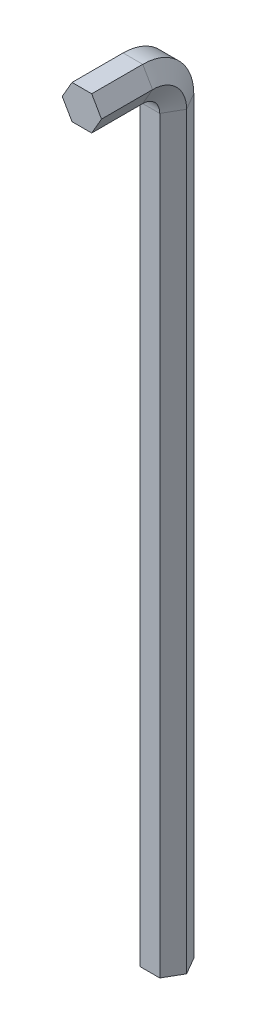
SolidWorks part; units mm, degrees
ref_plane "Front Plane" through (0, 0, 0) normal (0, 0, 1) x (1, 0, 0)
ref_plane "Top Plane" through (0, 0, 0) normal (0, 1, 0) x (1, 0, 0)
ref_plane "Right Plane" through (0, 0, 0) normal (1, 0, 0) x (0, 0, -1)
other "Center of Mass"
sketch "Sketch1" plane through (0, 0, 0) normal (0, 1, 0) x (1, 0, 0)
  line L1 (5.7735, 0) -> (2.8868, 5)
  line L2 (2.8868, 5) -> (-2.8868, 5)
  line L3 (-2.8868, 5) -> (-5.7735, 0)
  line L4 (-5.7735, 0) -> (-2.8868, -5)
  line L5 (-2.8868, -5) -> (2.8868, -5)
  line L6 (2.8868, -5) -> (5.7735, 0)
  circle A0 centre (0, 0) radius 5 construction
  dimension "D1" = 10
extrude "Boss-Extrude1" add sketch "Sketch1" along normal blind 220
sketch "Sketch2" plane through (0, 220, 0) normal (0, 1, 0) x (1, 0, 0)
  line L0 (-6.6103, -10) -> (7.1462, -10) construction
  line L1 (-2.8868, -5) -> (2.8868, -5) construction
  line L2 (-2.8868, 5) -> (-5.7735, 0) construction
  line L3 (2.8868, 5) -> (-2.8868, 5) construction
  line L4 (5.7735, 0) -> (2.8868, 5) construction
  line L5 (2.8868, -5) -> (5.7735, 0) construction
  line L6 (-5.7735, 0) -> (-2.8868, -5) construction
  line L7 (-2.8868, -5) -> (2.8868, -5)
  line L8 (-5.7735, 0) -> (-2.8868, -5)
  line L9 (-2.8868, 5) -> (-5.7735, 0)
  line L10 (2.8868, 5) -> (-2.8868, 5)
  line L11 (5.7735, 0) -> (2.8868, 5)
  line L12 (2.8868, -5) -> (5.7735, 0)
  dimension "D1" = 10
revolve "Revolve1" add sketch "Sketch2" angle 90 about L0
sketch "Sketch3" plane through (0, 0, 10) normal (0, 0, 1) x (1, 0, 0)
  line L0 (-5.7735, 230) -> (-2.8868, 225) construction
  line L1 (-2.8868, 225) -> (2.8868, 225) construction
  line L2 (2.8868, 225) -> (5.7735, 230) construction
  line L3 (5.7735, 230) -> (2.8868, 235) construction
  line L4 (2.8868, 235) -> (-2.8868, 235) construction
  line L5 (-2.8868, 235) -> (-5.7735, 230) construction
  line L6 (-5.7735, 230) -> (-2.8868, 225)
  line L7 (-2.8868, 225) -> (2.8868, 225)
  line L8 (2.8868, 225) -> (5.7735, 230)
  line L9 (5.7735, 230) -> (2.8868, 235)
  line L10 (2.8868, 235) -> (-2.8868, 235)
  line L11 (-2.8868, 235) -> (-5.7735, 230)
extrude "Boss-Extrude2" add sketch "Sketch3" along normal blind 15
